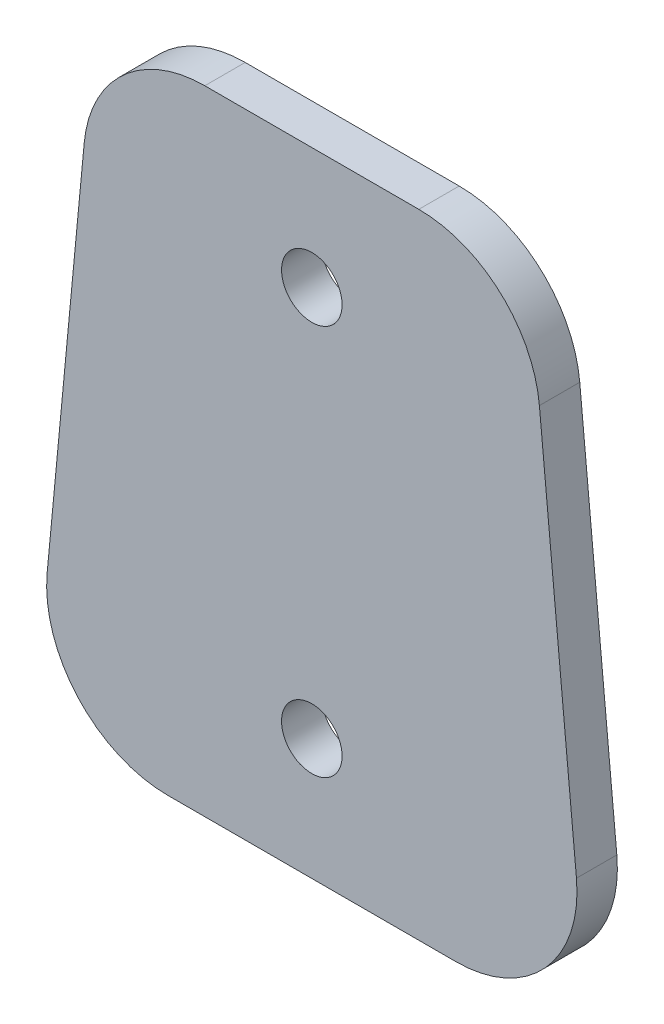
SolidWorks part; units mm, degrees
ref_plane "Front Plane" through (0, 0, 0) normal (0, 0, 1) x (1, 0, 0)
ref_plane "Top Plane" through (0, 0, 0) normal (0, 1, 0) x (1, 0, 0)
ref_plane "Right Plane" through (0, 0, 0) normal (1, 0, 0) x (0, 0, -1)
sketch "Sketch2" plane through (0, 0, 0) normal (0, 0, 1) x (1, 0, 0)
  line L1 (44.6253, 31.6332) -> (41.7109, 62.3672)
  line L3 (5.9141, 62.3672) -> (2.9997, 31.6332)
  line L4 (15.3966, 70.993) -> (32.2284, 70.993)
  line L5 (35.1428, 21.209) -> (12.4822, 21.209)
  circle A0 centre (23.8125, 30.734) radius 2.3813
  circle A1 centre (23.8125, 61.468) radius 2.3813
  arc A2 (12.4822, 21.209) -> (2.9997, 31.6332) centre (12.4822, 30.734) cw
  arc A3 (35.1428, 21.209) -> (44.6253, 31.6332) centre (35.1428, 30.734) ccw
  arc A4 (32.2284, 70.993) -> (41.7109, 62.3672) centre (32.2284, 61.468) cw
  arc A5 (15.3966, 70.993) -> (5.9141, 62.3672) centre (15.3966, 61.468) ccw
  dimension "D6" = 4.7625
  dimension "D7" = 4.7625
  dimension "D1" = 9.525
  dimension "D4" = 30.734
  dimension "D8" = 9.525
  dimension "D9" = 9.525
extrude "Boss-Extrude1" add sketch "Sketch2" along normal blind 3.175
